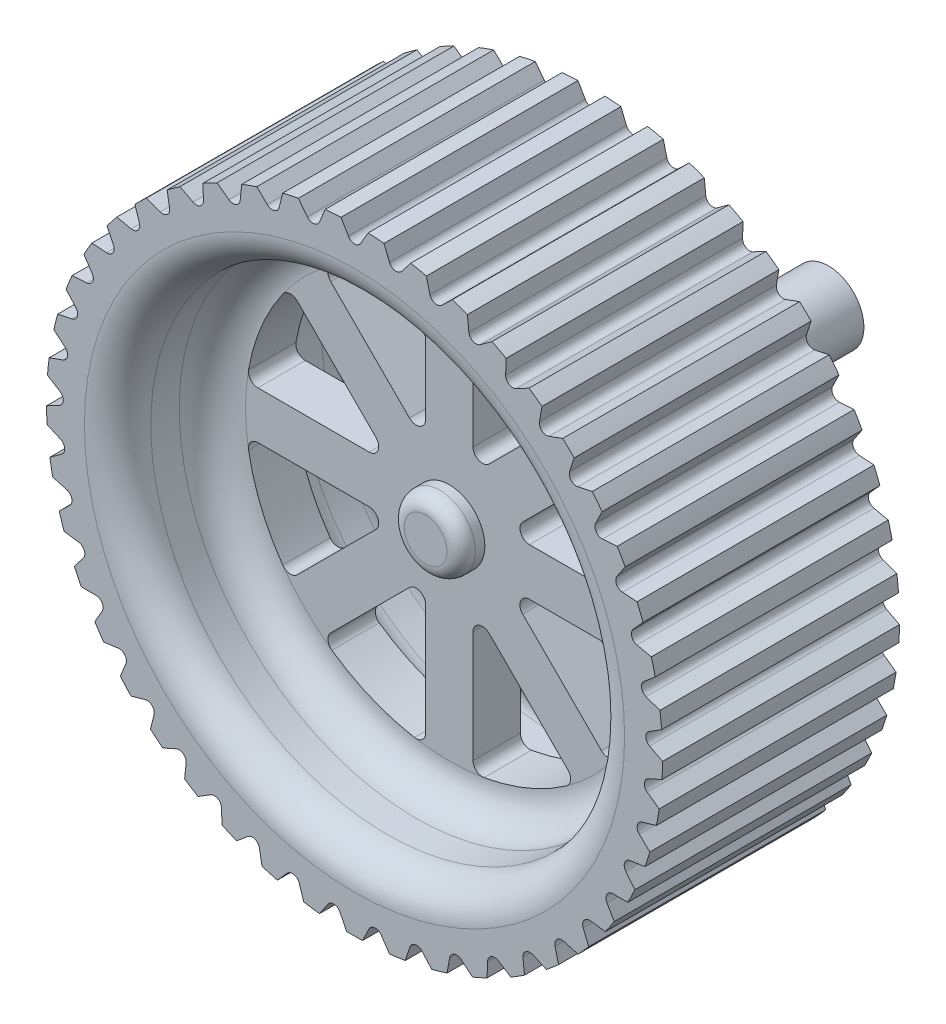
SolidWorks part; units mm, degrees
ref_plane "Front Plane" through (0, 0, 0) normal (0, 0, 1) x (1, 0, 0)
ref_plane "Top Plane" through (0, 0, 0) normal (0, 1, 0) x (1, 0, 0)
ref_plane "Right Plane" through (0, 0, 0) normal (1, 0, 0) x (0, 0, -1)
sketch "Sketch1" plane through (0, 0, 0) normal (0, 0, 1) x (1, 0, 0)
  circle A0 centre (0, 0) radius 7.5
  dimension "D1" = 15
extrude "Boss-Extrude1" add sketch "Sketch1" against normal blind 50
sketch "Sketch2" plane through (0, 0, 0) normal (0, 0, 1) x (1, 0, 0)
  circle A0 centre (0, 0) radius 65
  dimension "D1" = 130
extrude "Boss-Extrude2" add sketch "Sketch2" along normal blind 50
sketch "Sketch3" plane through (0, 0, 50) normal (0, 0, 1) x (1, 0, 0)
  line L0 (0, 65) -> (0, 60)
  line L1 (0, 60) -> (4.3301, 67.5)
  line L2 (4.3301, 67.5) -> (-4.3301, 67.5)
  line L3 (-4.3301, 67.5) -> (0, 60)
  line L4 (0, 65) -> (0, 0) construction
  circle A0 centre (0, 65) radius 2.5 construction
  circle A1 centre (0, 0) radius 65 construction
  dimension "D1" = 5
extrude "Cut-Extrude1" cut sketch "Sketch3" against normal up to next contours L1 L2 L3
fillet "Fillet1" radius 1.5 1 edges at (0, 60, 25)
pattern_circular "CirPattern1" count 45 over 360 about axis through (0, 0, 0) along (0, 0, 1) of "Cut-Extrude1", "Fillet1"
sketch "Sketch5" plane through (0, 0, 50) normal (0, 0, 1) x (1, 0, 0)
  circle A0 centre (0, 0) radius 50
  dimension "D1" = 100
extrude "Cut-Extrude2" cut sketch "Sketch5" against normal blind 20
sketch "Sketch6" plane through (0, 0, 0) normal (0, 0, -1) x (-1, 0, 0)
  circle A0 centre (0, 0) radius 50
  circle A1 centre (0, 0) radius 7.5
  dimension "D1" = 100
  dimension "D2" = 15
extrude "Cut-Extrude6" cut sketch "Sketch6" against normal blind 20
fillet "Fillet2" radius 7 4 edges at (50, 0, 30) (50, 0, 50) (-50, 0, 20) (-50, 0, 0)
ref_plane "Plane1" through (0, 0, 25) normal (0, 0, 1) x (1, 0, 0)
sketch "Sketch7" plane through (0, 0, 30) normal (0, 0, 1) x (1, 0, 0)
  circle A0 centre (0, 0) radius 7.5
  dimension "D1" = 15
extrude "Boss-Extrude3" add sketch "Sketch7" along normal blind 5
sketch "Sketch8" plane through (0, 0, 30) normal (0, 0, 1) x (1, 0, 0)
  line L0 (0, 45.5902) -> (0, 0) construction
  line L1 (-5, 5.5902) -> (5, 5.5902)
  line L2 (-5, 5.5902) -> (-5, 45.5902)
  line L3 (-5, 45.5902) -> (5, 45.5902)
  line L4 (5, 5.5902) -> (5, 45.5902)
  line L5 (0.4173, 7.4884) -> (28.7016, 35.7727)
  line L6 (0.4173, 7.4884) -> (7.4884, 0.4173)
  line L7 (7.4884, 0.4173) -> (35.7727, 28.7016)
  line L8 (28.7016, 35.7727) -> (35.7727, 28.7016)
  line L9 (5.5902, 5) -> (45.5902, 5)
  line L10 (5.5902, 5) -> (5.5902, -5)
  line L11 (5.5902, -5) -> (45.5902, -5)
  line L12 (45.5902, 5) -> (45.5902, -5)
  line L13 (7.4884, -0.4173) -> (35.7727, -28.7016)
  line L14 (7.4884, -0.4173) -> (0.4173, -7.4884)
  line L15 (0.4173, -7.4884) -> (28.7016, -35.7727)
  line L16 (35.7727, -28.7016) -> (28.7016, -35.7727)
  line L17 (5, -5.5902) -> (5, -45.5902)
  line L18 (5, -5.5902) -> (-5, -5.5902)
  line L19 (-5, -5.5902) -> (-5, -45.5902)
  line L20 (5, -45.5902) -> (-5, -45.5902)
  line L21 (-0.4173, -7.4884) -> (-28.7016, -35.7727)
  line L22 (-0.4173, -7.4884) -> (-7.4884, -0.4173)
  line L23 (-7.4884, -0.4173) -> (-35.7727, -28.7016)
  line L24 (-28.7016, -35.7727) -> (-35.7727, -28.7016)
  line L25 (-5.5902, -5) -> (-45.5902, -5)
  line L26 (-5.5902, -5) -> (-5.5902, 5)
  line L27 (-5.5902, 5) -> (-45.5902, 5)
  line L28 (-45.5902, -5) -> (-45.5902, 5)
  line L29 (-7.4884, 0.4173) -> (-35.7727, 28.7016)
  line L30 (-7.4884, 0.4173) -> (-0.4173, 7.4884)
  line L31 (-0.4173, 7.4884) -> (-28.7016, 35.7727)
  line L32 (-35.7727, 28.7016) -> (-28.7016, 35.7727)
  circle A0 centre (0, 0) radius 7.5 construction
  circle A1 centre (0, 0) radius 43
  point P7 (0, 5.5902)
  point P8 (0, 0)
  point P42 (0, 0)
  circle M36 centre (0, 0) radius 43
  dimension "D3" = 86
  dimension "D1" = 10
  dimension "D2" = 40
  dimension "D4" = 8
extrude "Cut-Extrude7" cut sketch "Sketch8" against normal up to next contours L31 L2 M36 | L4 L5 M36 | L7 L9 M36 | L11 L13 M36 | L15 L17 M36 | L19 L21 M36 | L23 L25 M36 | L27 L29 M36
fillet "Fillet3" radius 2 24 edges at (33.7349, -26.6638, 25) (42.7083, -5, 25) (33.7349, 26.6638, 25) (26.6638, 33.7349, 25) (5, 42.7083, 25) (-5, 42.7083, 25) (-33.7349, 26.6638, 25) (-42.7083, -5, 25) (-33.7349, -26.6638, 25) (-26.6638, 33.7349, 25) (-42.7083, 5, 25) (-5, -42.7083, 25) (-26.6638, -33.7349, 25) (5, -42.7083, 25) (26.6638, -33.7349, 25) (42.7083, 5, 25) (-5, 12.0711, 25) (-12.0711, 5, 25) (-12.0711, -5, 25) (-5, -12.0711, 25) (5, -12.0711, 25) (12.0711, -5, 25) (12.0711, 5, 25) (5, 12.0711, 25)
fillet "Fillet4" radius 3 1 edges at (7.5, 0, 35)
